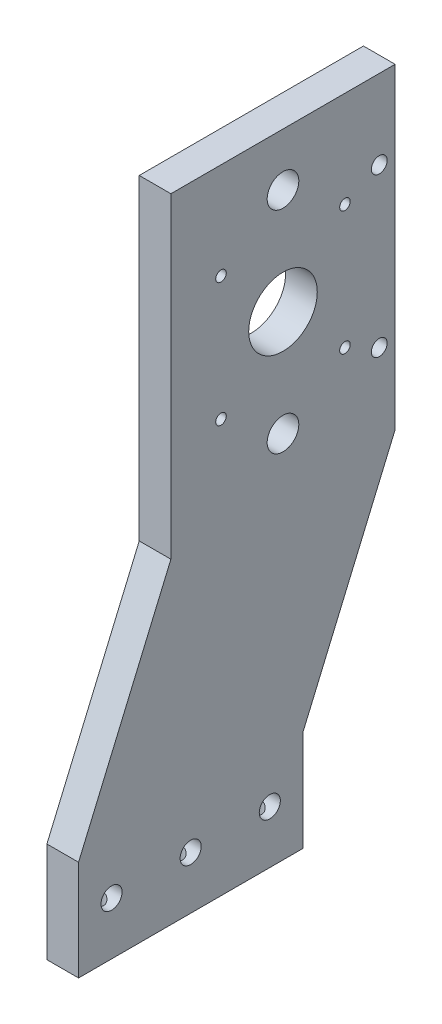
SolidWorks part; units mm, degrees
material "Beech"
ref_plane "Front Plane" through (0, 0, 0) normal (0, 0, 1) x (1, 0, 0)
ref_plane "Top Plane" through (0, 0, 0) normal (0, 1, 0) x (1, 0, 0)
ref_plane "Right Plane" through (0, 0, 0) normal (1, 0, 0) x (0, 0, -1)
sketch "Sketch1" plane through (0, 0, 0) normal (1, 0, 0) x (0, 0, -1)
  line L0 (120, 240) -> (35, 240)
  line L1 (0, 0) -> (85, 0)
  line L2 (0, 0) -> (0, 38)
  line L4 (0, 38) -> (35, 120)
  line L6 (35, 120) -> (35, 240)
  line L7 (85, 0) -> (85, 38)
  line L8 (120, 240) -> (120, 120)
  line L9 (85, 38) -> (120, 120)
  dimension "D1" = 85
  dimension "D2" = 38
  dimension "D3" = 120
  dimension "D4" = 35
  dimension "D5" = 120
  dimension "D6" = 85
  dimension "D7" = 240
  dimension "D8" = 38
extrude "Boss-Extrude1" add sketch "Sketch1" along normal blind 12
sketch "Sketch2" plane through (0, 0, 0) normal (-1, 0, 0) x (0, 0, 1)
  line L0 (8.143, 20) -> (-94.4015, 20) construction
  line L1 (0, 0) -> (-85, 0) construction
  line L2 (-42.5, -2.4224) -> (-42.5, 25.4228) construction
  circle A0 centre (-42.5, 20) radius 4
  circle A1 centre (-72.5, 20) radius 4
  circle A2 centre (-12.5, 20) radius 4
  dimension "D2" = 8
  dimension "D3" = 8
  dimension "D4" = 8
  dimension "D5" = 30
  dimension "D6" = 30
  dimension "D1" = 20
extrude "Cut-Extrude1" cut sketch "Sketch2" against normal up to next
sketch "Sketch3" plane through (0, 0, 0) normal (0, -1, 0) x (1, 0, 0)
  line L0 (6, -86.3546) -> (6, 3.2892) construction
  line L1 (-3.8727, -42.5) -> (14.9752, -42.5) construction
  circle A0 centre (6, -42.5) radius 3
  circle A1 centre (6, -72.5) radius 3
  circle A2 centre (6, -12.5) radius 3
  dimension "D1" = 6
  dimension "D2" = 6
  dimension "D3" = 6
  dimension "D4" = 30
  dimension "D5" = 30
extrude "Cut-Extrude2" cut sketch "Sketch3" against normal up to next
sketch "Sketch4" plane through (0, 0, 0) normal (-1, 0, 0) x (0, 0, 1)
  line L1 (-77.5, 261.9114) -> (-77.5, 131.8067) construction
  line L3 (-120, 240) -> (-35, 240) construction
  line L4 (-96.7776, 180) -> (-159.4061, 180) construction
  line L5 (-77.5, 221.9158) -> (-77.5, 210.4215) construction
  line L6 (-101, 269.2685) -> (-101, 210.9179) construction
  line L7 (-54, 269.2685) -> (-54, 210.4215) construction
  line L8 (-96.7776, 203.5) -> (-159.4061, 203.5) construction
  line L9 (-96.7776, 156.5) -> (-159.4061, 156.5) construction
  line L10 (-101, 215.3774) -> (-101, 210.4215) construction
  line L11 (-77.5, 215.3774) -> (-77.5, 210.4215) construction
  line L12 (-54, 215.3774) -> (-54, 210.4215) construction
  line L13 (-35, 240) -> (-35, 120) construction
  line L14 (-120, 120) -> (-120, 240) construction
  circle A0 centre (-77.5, 180) radius 13
  circle A1 centre (-77.5, 220) radius 6
  circle A2 centre (-77.5, 140) radius 6
  circle A3 centre (-101, 203.5) radius 2
  circle A4 centre (-54, 203.5) radius 2
  circle A5 centre (-101, 156.5) radius 2
  circle A6 centre (-54, 156.5) radius 2
  point P2 (-85, 0)
  dimension "D1" = 26
  dimension "D2" = 42.5
  dimension "D3" = 12
  dimension "D4" = 12
  dimension "D5" = 80
  dimension "D6" = 20
  dimension "D7" = 40
  dimension "D13" = 4
  dimension "D14" = 4
  dimension "D15" = 4
  dimension "D16" = 4
  dimension "D8" = 42.5
  dimension "D9" = 23.5
  dimension "D10" = 23.5
  dimension "D11" = 23.5
  dimension "D12" = 23.5
extrude "Cut-Extrude3" cut sketch "Sketch4" against normal up to next
sketch "Sketch5" plane through (0, 0, 0) normal (-1, 0, 0) x (0, 0, 1)
  line L0 (-114, 306.8169) -> (-114, 173.767) construction
  line L1 (-87.0007, 180) -> (-32.2658, 180) construction
  line L2 (-120, 120) -> (-120, 240) construction
  circle A0 centre (-114, 210) radius 3
  circle A1 centre (-114, 150) radius 3
  dimension "D1" = 6
  dimension "D2" = 6
  dimension "D3" = 30
  dimension "D4" = 60
  dimension "D5" = 6
extrude "Cut-Extrude4" cut sketch "Sketch5" against normal up to next
